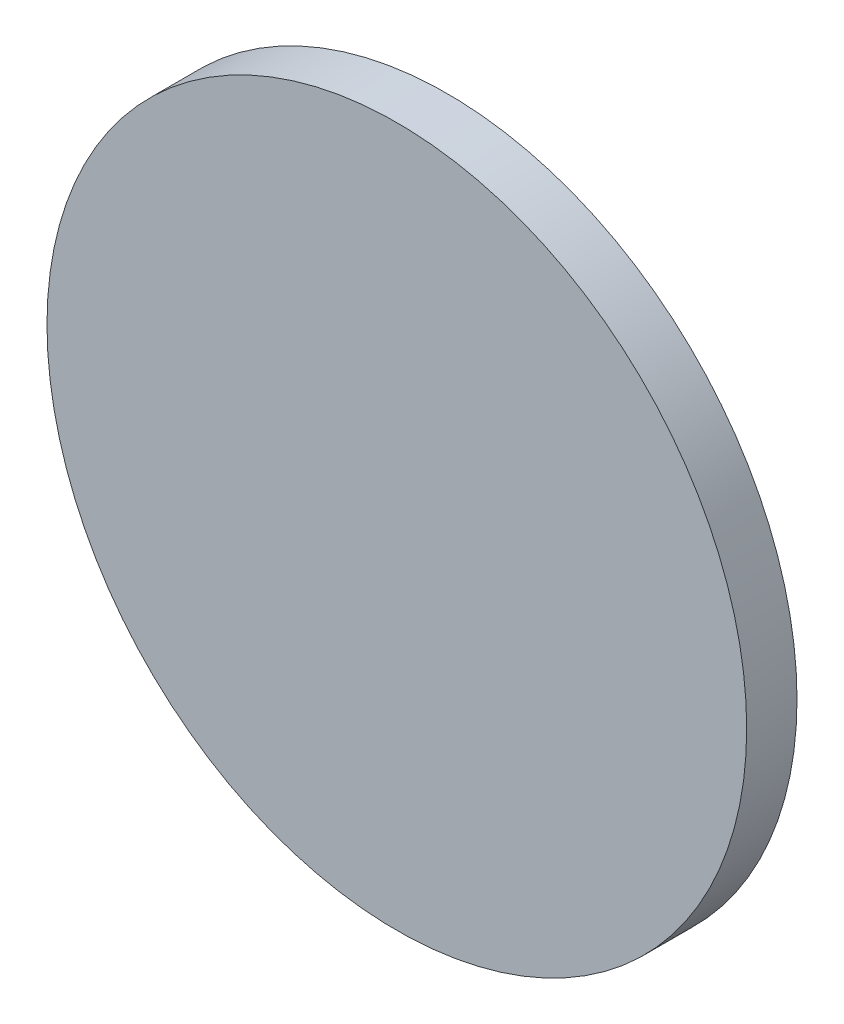
SolidWorks part; units mm, degrees
ref_plane "Front Plane" through (0, 0, 0) normal (0, 0, 1) x (1, 0, 0)
ref_plane "Top Plane" through (0, 0, 0) normal (0, 1, 0) x (1, 0, 0)
ref_plane "Right Plane" through (0, 0, 0) normal (1, 0, 0) x (0, 0, -1)
sketch "Sketch3" plane through (0, 0, 0) normal (0, 0, 1) x (1, 0, 0)
  circle A0 centre (0, 0) radius 38.25
  dimension "D1" = 76.5
extrude "Boss-Extrude1" add sketch "Sketch3" along normal blind 5.5
